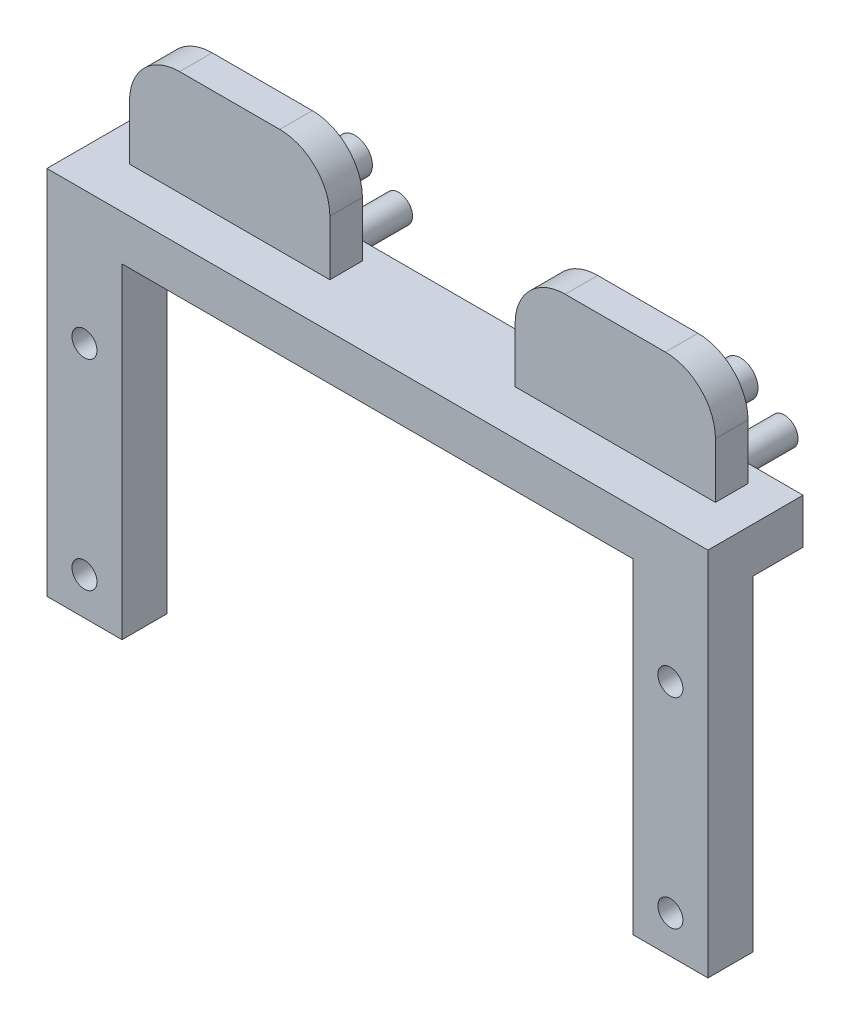
SolidWorks part; units mm, degrees
ref_plane "Front Plane" through (0, 0, 0) normal (0, 0, 1) x (1, 0, 0)
ref_plane "Top Plane" through (0, 0, 0) normal (0, 1, 0) x (1, 0, 0)
ref_plane "Right Plane" through (0, 0, 0) normal (1, 0, 0) x (0, 0, -1)
sketch "Sketch1" plane through (0, 0, 0) normal (0, 1, 0) x (1, 0, 0)
  line L1 (0, 8.5) -> (66, 8.5)
  line L2 (0, 8.5) -> (0, 27.5)
  line L3 (0, 27.5) -> (66, 27.5)
  line L4 (66, 8.5) -> (66, 27.5)
  point P5 (0, 0)
  point P6 (0, 0)
  point P29 (0, 0)
  dimension "D1" = 19
  dimension "D2" = 66
extrude "Boss-Extrude2" add sketch "Sketch1" along normal blind 8 and the other way blind 1
sketch "Sketch3" plane through (0, 0, -27.5) normal (0, 0, -1) x (-1, 0, 0)
  line L1 (-55, -1) -> (-37.5, -1) construction
  line L2 (-55, -1) -> (-55, 3.5) construction
  line L3 (-55, 3.5) -> (-37.5, 3.5) construction
  line L4 (-37.5, -1) -> (-37.5, 3.5) construction
  circle A0 centre (-37.5, 3.5) radius 2.75
  circle A1 centre (-17.5, 3.5) radius 2.75
  dimension "D3" = 5.5
  dimension "D1" = 4.5
  dimension "D2" = 17.5
  dimension "D4" = 2
extrude "Boss-Extrude3" add sketch "Sketch3" along normal blind 13.75
sketch "Sketch4" plane through (0, 8, 0) normal (0, 1, 0) x (1, 0, 0)
  line L2 (27.5, 27.5) -> (27.5, 0) construction
  line L4 (55, 24) -> (55, 17.5)
  line L9 (27.5, 27.5) -> (27.5, 24)
  line L11 (27.5, 24) -> (32, 24)
  line L12 (27.5, 24) -> (27.5, 17.5)
  line L13 (27.5, 17.5) -> (32, 17.5)
  line L14 (32, 24) -> (32, 17.5)
  line L15 (27.5, 24) -> (23, 24)
  line L16 (27.5, 24) -> (27.5, 17.5)
  line L17 (27.5, 17.5) -> (23, 17.5)
  line L18 (23, 24) -> (23, 17.5)
  dimension "D4" = 3.5
  dimension "D5" = 4.5
  dimension "D6" = 6.5
  dimension "D7" = 4.5
extrude "Boss-Extrude4" add sketch "Sketch4" along normal blind 15 contours L15 L18 L17 L12 | L14 L11 L12 L13
sketch "Sketch5" plane through (0, 0, -24) normal (0, 0, -1) x (-1, 0, 0)
  line L0 (-27.5, 8) -> (-27.5, 16)
  circle A0 centre (-27.5, 16) radius 3.5
  circle A1 centre (-25.7747, 12.9548) radius 0.161
extrude "Boss-Extrude5" add sketch "Sketch5" along normal blind 8.5
sketch "Sketch6" plane through (0, 0, -32.5) normal (0, 0, -1) x (-1, 0, 0)
  line L0 (-30.9402, 15.3557) -> (-30.9492, 15.4061)
  arc A0 (-25.6364, 13.0374) -> (-25.9166, 12.8787) centre (-27.5, 16) ccw construction
sketch "Sketch8" plane through (0, 23, 0) normal (0, 1, 0) x (1, 0, 0)
  line L1 (32, 24) -> (23, 24)
  line L2 (32, 24) -> (32, 17.5)
  line L3 (32, 17.5) -> (23, 17.5)
  line L4 (23, 24) -> (23, 17.5)
extrude "Boss-Extrude6" add sketch "Sketch8" along normal blind 6
sketch "Sketch9" plane through (0, 8, 0) normal (0, 1, 0) x (1, 0, 0)
  line L0 (27.5, 17.5) -> (47.5, 17.5)
  line L3 (47.5, 17.5) -> (7.5, 17.5)
  line L4 (47.5, 17.5) -> (47.5, 24)
  line L5 (47.5, 24) -> (7.5, 24)
  line L6 (7.5, 17.5) -> (7.5, 24)
  dimension "D1" = 20
  dimension "D2" = 6.5
  dimension "D3" = 40
extrude "Boss-Extrude7" add sketch "Sketch9" along normal blind 21
sketch "Sketch10" plane through (0, 0, -24) normal (0, 0, -1) x (-1, 0, 0)
  line L0 (-27.5, 17) -> (-7.5, 17)
  line L2 (-7.5, 17) -> (-47.5, 17)
  line L4 (-17.5, 3.5) -> (-17.5, 17)
  line L5 (-37.5, 3.5) -> (-37.5, 17)
  circle A0 centre (-17.5, 17) radius 3.5
  circle A1 centre (-37.5, 17) radius 3.5
  dimension "D1" = 7
  dimension "D2" = 7
extrude "Boss-Extrude8" add sketch "Sketch10" along normal blind 8.5 contours L2 A0 | L2 A0 L4 | L2 A1 | L2 A1 L5 | L5 A1 L2
sketch "Sketch12" plane through (0, 0, -32.5) normal (0, 0, -1) x (-1, 0, 0)
  circle A0 centre (-27.5, 16) radius 3.5
extrude "Cut-Extrude2" cut sketch "Sketch12" against normal blind 8.5
fillet "Fillet1" radius 10 2 edges at (47.5, 29, -20.75) (7.5, 29, -20.75)
sketch "Sketch14" plane through (0, -1, 0) normal (0, -1, 0) x (1, 0, 0)
  line L0 (0, -8.5) -> (66, -8.5) construction
  line L1 (0, -17.5) -> (15, -17.5)
  line L2 (0, -17.5) -> (0, -8.5)
  line L3 (0, -8.5) -> (15, -8.5)
  line L4 (15, -17.5) -> (15, -8.5)
  dimension "D1" = 15
  dimension "D2" = 9
extrude "Boss-Extrude10" add sketch "Sketch14" along normal blind 65
sketch "Sketch15" plane through (0, 0, -17.5) normal (0, 0, -1) x (-1, 0, 0)
  line L0 (-15, -66) -> (-15, -1) construction
  line L1 (0, -66) -> (-15, -66) construction
  circle A0 centre (-7.5, -18.5) radius 2.5
  circle A1 centre (-7.5, -58.5) radius 2.5
  dimension "D1" = 5
  dimension "D2" = 5
  dimension "D3" = 7.5
  dimension "D4" = 7.5
  dimension "D5" = 47.5
  dimension "D6" = 7.5
extrude "Cut-Extrude3" cut sketch "Sketch15" against normal up to next
mirror "Mirror3" about plane through (66, -1, -8.5) normal (1, 0, 0) of "Boss-Extrude2", "Boss-Extrude3", "Boss-Extrude4", "Boss-Extrude6", "Boss-Extrude7", "Boss-Extrude8", "Fillet1", "Boss-Extrude10", "Cut-Extrude3"
